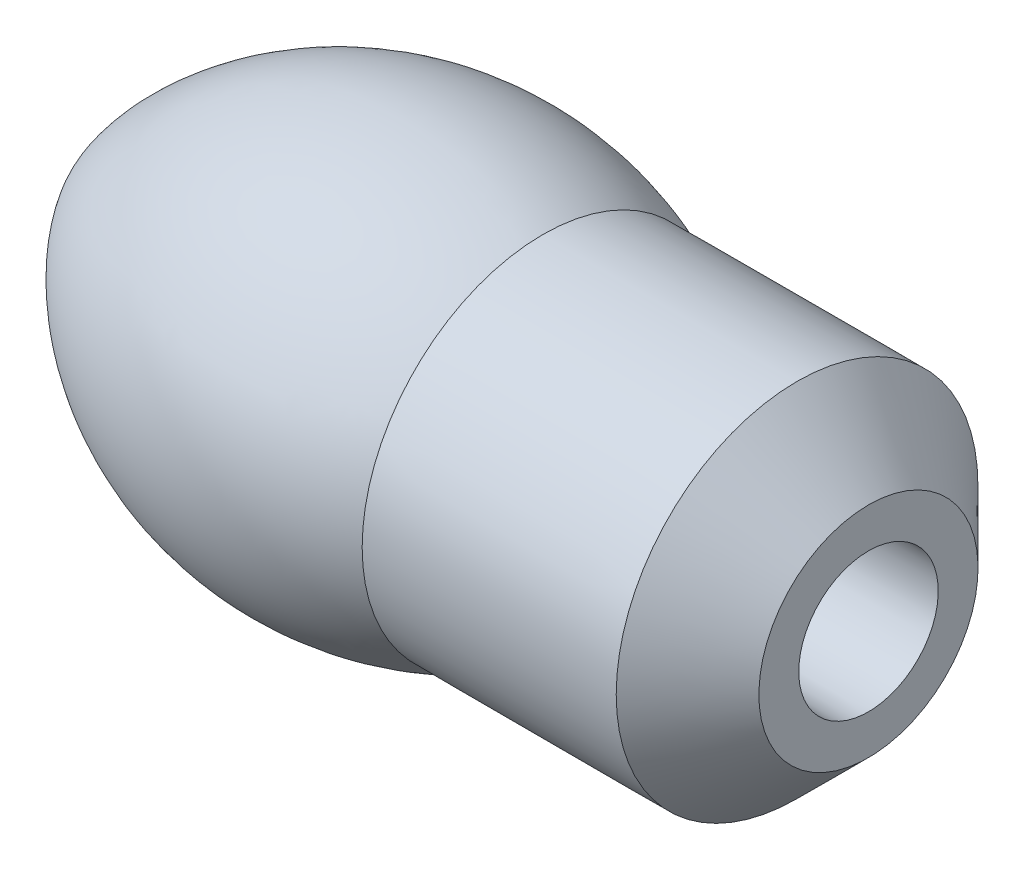
SolidWorks part; units mm, degrees
ref_plane "Front Plane" through (0, 0, 0) normal (0, 0, 1) x (1, 0, 0)
ref_plane "Top Plane" through (0, 0, 0) normal (0, 1, 0) x (1, 0, 0)
ref_plane "Right Plane" through (0, 0, 0) normal (1, 0, 0) x (0, 0, -1)
sketch "Sketch1" plane through (0, 0, 0) normal (0, 0, 1) x (1, 0, 0)
  line L2 (0, 26.2205) -> (60, 26.2205)
  line L4 (60, 26.2205) -> (60, 41.2205)
  line L6 (60, 41.2205) -> (33.1299, 68.0906)
  line L7 (33.1299, 68.0906) -> (-62.6465, 68.0906)
  line L11 (-251.2725, 0.2205) -> (-237.0271, 0.2205) construction
  line L12 (-237.0271, 0.2205) -> (93.6447, 0.2205) construction
  line L13 (0, 26.2205) -> (0, 0)
  line L14 (0, 0) -> (-237.0271, 0.2205)
  arc A3 (-62.6465, 68.0906) -> (-237.0271, 0.2205) centre (-115.9017, -53.0347) ccw
  dimension "D3" = 60
  dimension "D4" = 15
  dimension "D6" = 135
  dimension "D7" = 38
revolve "Revolve1" add sketch "Sketch1" angle 360 about L14
